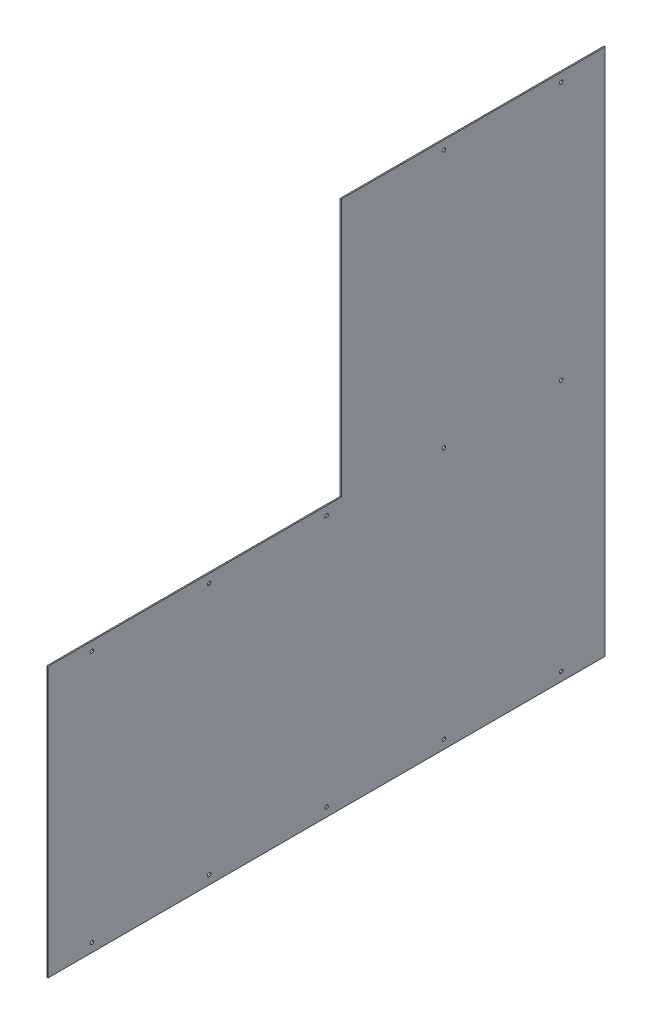
SolidWorks part; units mm, degrees
ref_plane "Front Plane" through (0, 0, 0) normal (0, 0, 1) x (1, 0, 0)
ref_plane "Top Plane" through (0, 0, 0) normal (0, 1, 0) x (1, 0, 0)
ref_plane "Right Plane" through (0, 0, 0) normal (1, 0, 0) x (0, 0, -1)
sketch "Sketch1" plane through (0, 0, 0) normal (1, 0, 0) x (0, 0, -1)
  line L1 (-475, -230) -> (475, -230)
  line L2 (-475, -230) -> (-475, 230)
  line L3 (-475, 230) -> (475, 230)
  line L4 (475, -230) -> (475, 230)
  line L5 (-475, -230) -> (475, 230) construction
  line L6 (-475, 230) -> (475, -230) construction
  point P0 (0, 0)
  dimension "D1" = 950
  dimension "D2" = 460
extrude "Boss-Extrude2" add sketch "Sketch1" along normal blind 2
sketch "Sketch3" plane through (2, 0, 0) normal (1, 0, 0) x (0, 0, -1)
  line L0 (475, 230) -> (-475, 230) construction
  line L1 (-475, 230) -> (-475, -230) construction
  line L3 (-475, 0) -> (475, 0) construction
  line L4 (475, -230) -> (475, 230) construction
  circle A0 centre (-400, 215) radius 3
  circle A1 centre (-200, 215) radius 3
  circle A2 centre (0, 215) radius 3
  circle A3 centre (200, 215) radius 3
  circle A4 centre (400, 215) radius 3
  circle A5 centre (400, -215) radius 3
  circle A6 centre (0, -215) radius 3
  circle A7 centre (200, -215) radius 3
  circle A8 centre (-200, -215) radius 3
  circle A9 centre (-400, -215) radius 3
  dimension "D1" = 6
  dimension "D2" = 15
  dimension "D3" = 75
  dimension "D4" = 5
extrude "Cut-Extrude1" cut sketch "Sketch3" against normal blind 2
sketch "Sketch5" plane through (2, 0, 0) normal (1, 0, 0) x (0, 0, -1)
  line L0 (475, 230) -> (-475, 230) construction
  line L1 (475, -230) -> (475, 230) construction
  line L2 (25, 230) -> (25, 670)
  line L3 (25, 670) -> (475, 670)
  line L4 (475, 670) -> (475, 230)
  line L5 (25, 230) -> (475, 230)
  line L6 (250, 670) -> (250, 230) construction
  circle A8 centre (400, 655) radius 3
  circle A9 centre (200, 655) radius 3
  point P0 (25, 230)
  dimension "D7" = 6
  dimension "D1" = 450
  dimension "D2" = 440
  dimension "D8" = 15
  dimension "D9" = 75
extrude "Boss-Extrude3" add sketch "Sketch5" against normal blind 2
